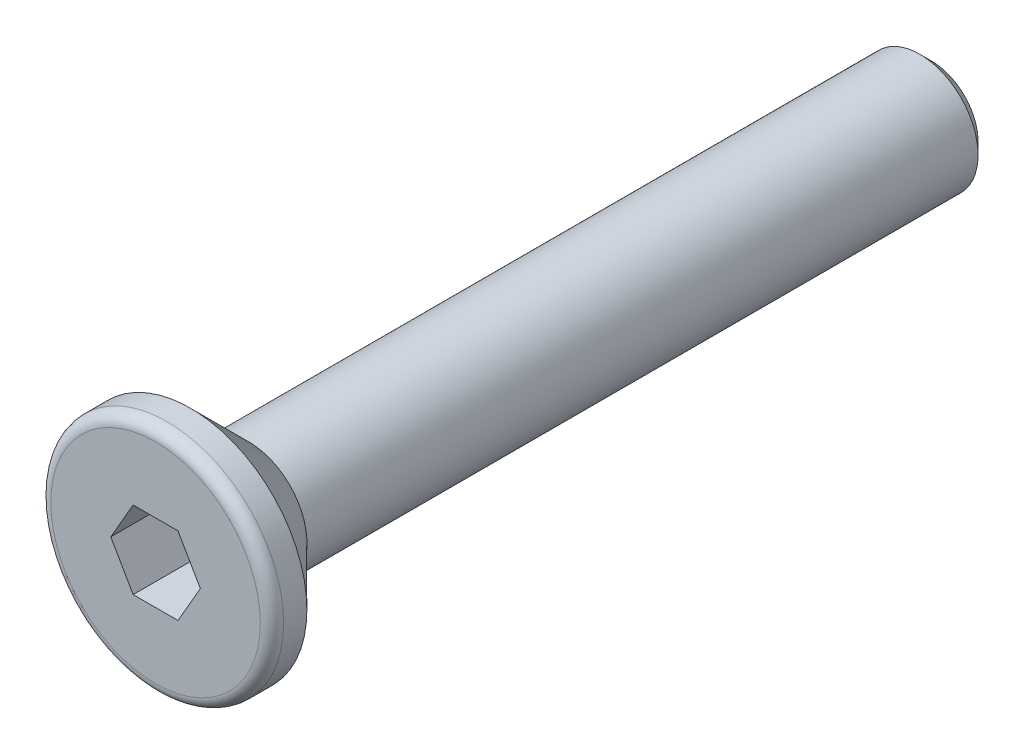
SolidWorks part; units mm, degrees
ref_plane "前视基准面" through (0, 0, 0) normal (0, 0, 1) x (1, 0, 0)
ref_plane "上视基准面" through (0, 0, 0) normal (0, 1, 0) x (1, 0, 0)
ref_plane "右视基准面" through (0, 0, 0) normal (1, 0, 0) x (0, 0, -1)
sketch "草图1" plane through (0, 0, 0) normal (1, 0, 0) x (0, 0, -1)
  line L0 (-10, 0) -> (-10, 3)
  line L1 (-10, 3) -> (-9.1, 3)
  line L2 (-9.1, 3) -> (-7.6, 1.5)
  line L3 (-7.6, 1.5) -> (9.7, 1.5)
  line L4 (9.7, 1.5) -> (10, 1.2)
  line L5 (10, 1.2) -> (10, 0)
  line L6 (10, 0) -> (-10, 0)
  dimension "D1" = 20
  dimension "D2" = 3
  dimension "D3" = 45
  dimension "D4" = 0.3
  dimension "D5" = 2.4
  dimension "D6" = 1.5
revolve "旋转1" add sketch "草图1" angle 360 about L6
sketch "草图2" plane through (0, 0, 10) normal (0, 0, 1) x (1, 0, 0)
  line L1 (1.1547, 0) -> (0.5774, 1)
  line L2 (0.5774, 1) -> (-0.5774, 1)
  line L3 (-0.5774, 1) -> (-1.1547, 0)
  line L4 (-1.1547, 0) -> (-0.5774, -1)
  line L5 (-0.5774, -1) -> (0.5774, -1)
  line L6 (0.5774, -1) -> (1.1547, 0)
  circle A0 centre (0, 0) radius 1 construction
  dimension "D1" = 2
extrude "切除-拉伸1" cut sketch "草图2" against normal blind 1.5
fillet "圆角1" radius 0.3 1 edges at (-3, 0, 10)
